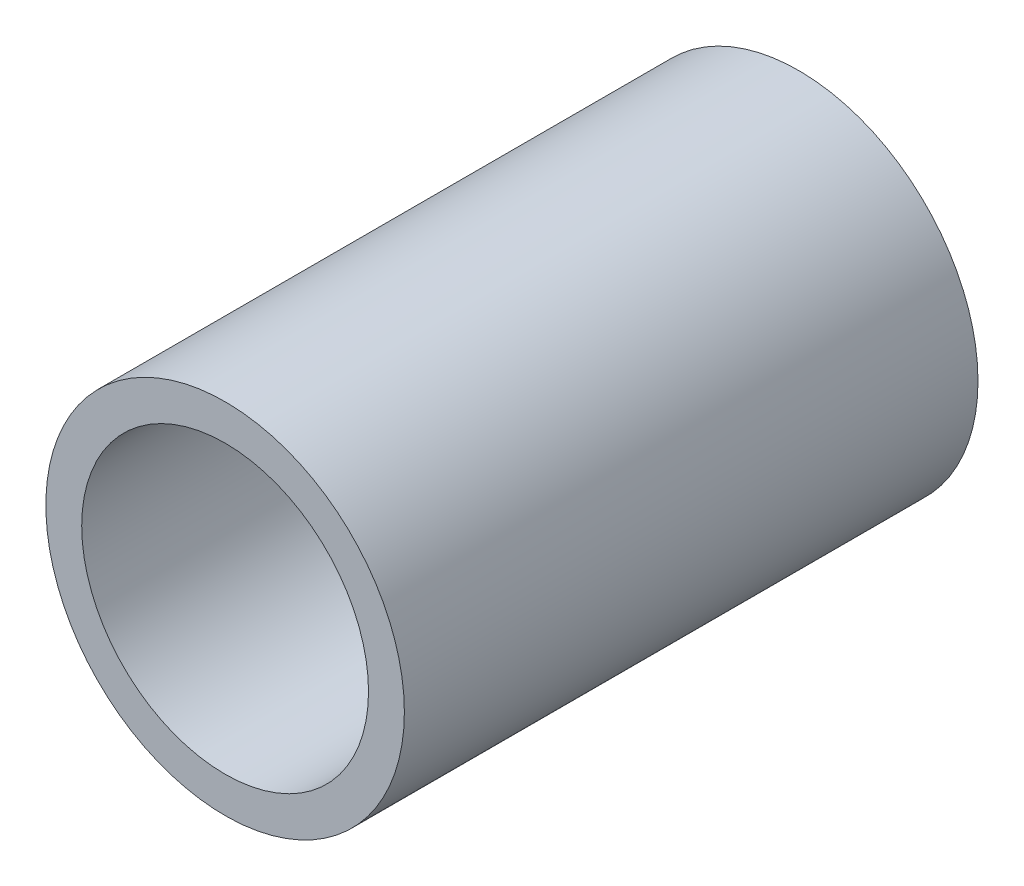
SolidWorks part; units mm, degrees
ref_plane "Front Plane" through (0, 0, 0) normal (0, 0, 1) x (1, 0, 0)
ref_plane "Top Plane" through (0, 0, 0) normal (0, 1, 0) x (1, 0, 0)
ref_plane "Right Plane" through (0, 0, 0) normal (1, 0, 0) x (0, 0, -1)
sketch "Sketch1" plane through (0, 0, 0) normal (0, 0, 1) x (1, 0, 0)
  circle A0 centre (0, 0) radius 7.5
  circle A1 centre (0, 0) radius 6
  dimension "D1" = 12
  dimension "D2" = 15
extrude "Boss-Extrude1" add sketch "Sketch1" along normal mid plane 24
